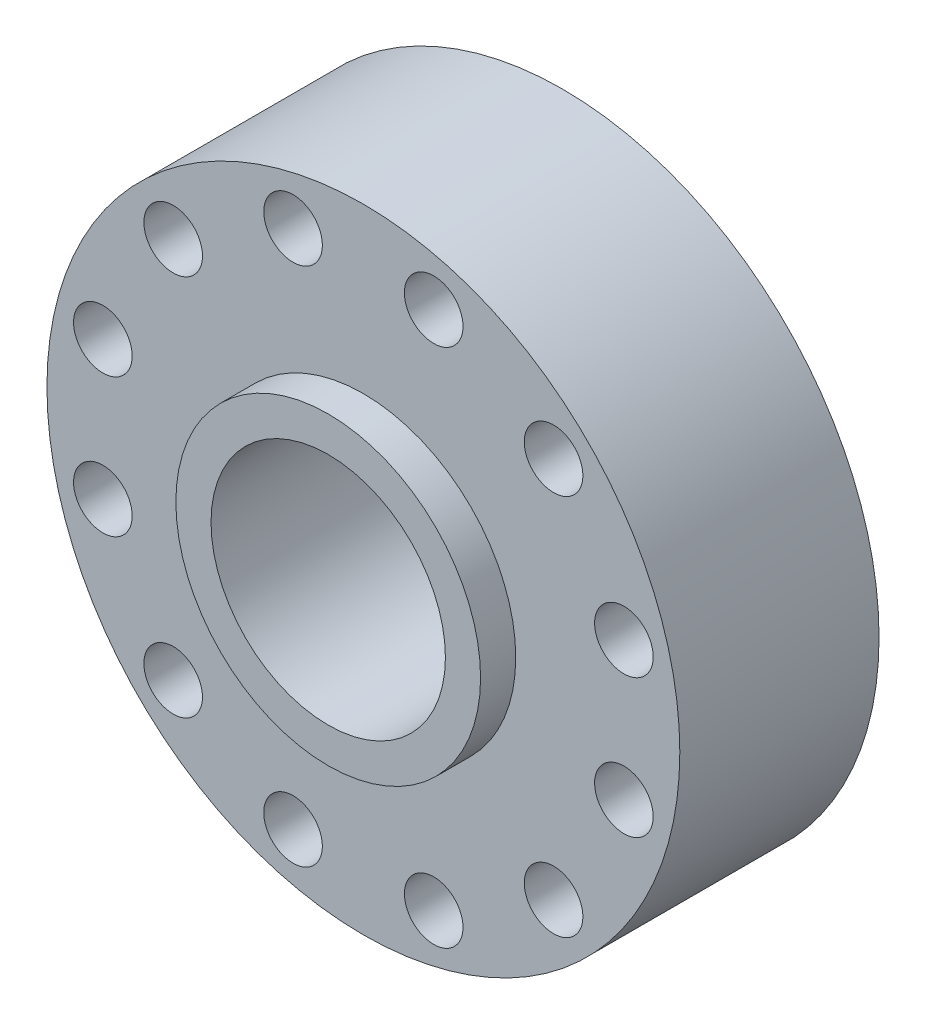
SolidWorks part; units mm, degrees
ref_plane "前视基准面" through (0, 0, 0) normal (0, 0, 1) x (1, 0, 0)
ref_plane "上视基准面" through (0, 0, 0) normal (0, 1, 0) x (1, 0, 0)
ref_plane "右视基准面" through (0, 0, 0) normal (1, 0, 0) x (0, 0, -1)
sketch "草图3" plane through (0, 0, 0) normal (0, 0, 1) x (1, 0, 0)
  circle A0 centre (0, 0) radius 27
  dimension "D1" = 54
extrude "凸台-拉伸1" add sketch "草图3" along normal mid plane 17
sketch "草图5" plane through (0, 0, -8.5) normal (0, 0, -1) x (-1, 0, 0)
  circle A0 centre (0, 0) radius 13
  dimension "D1" = 26
extrude "切除-拉伸2" cut sketch "草图5" against normal through all
sketch "草图8" plane through (0, 0, 0) normal (0, 0, 1) x (1, 0, 0)
  circle A0 centre (0, 0) radius 13
  circle A1 centre (0, 0) radius 10
  dimension "D1" = 26
  dimension "D2" = 20
extrude "凸台-拉伸2" add sketch "草图8" along normal mid plane 23
sketch "草图9" plane through (0, 0, -8.5) normal (0, 0, -1) x (-1, 0, 0)
  line L0 (0, 0) -> (0, 50000) construction
  circle A0 centre (0, 0) radius 23 construction
  circle A1 centre (-6, 22.2036) radius 2.5
  circle A2 centre (6, 22.2036) radius 2.5
  dimension "D1" = 46
  dimension "D2" = 5
  dimension "D4" = 5
  dimension "D3" = 6
  dimension "D5" = 6
extrude "切除-拉伸3" cut sketch "草图9" against normal up to next
pattern_circular "阵列(圆周)2" count 6 over 360 about axis through (0, 0, 0) along (0, 0, 1) of "切除-拉伸3"
